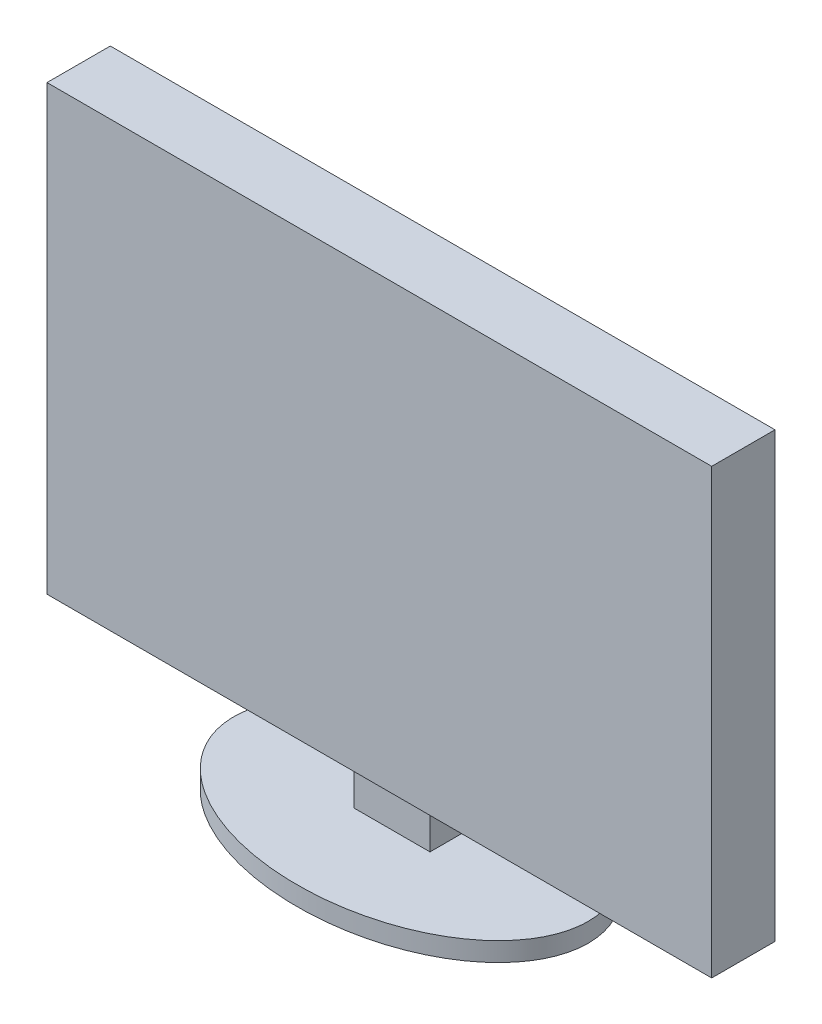
SolidWorks part; units mm, degrees
ref_plane "Front Plane" through (0, 0, 0) normal (0, 0, 1) x (1, 0, 0)
ref_plane "Top Plane" through (0, 0, 0) normal (0, 1, 0) x (1, 0, 0)
ref_plane "Right Plane" through (0, 0, 0) normal (1, 0, 0) x (0, 0, -1)
sketch "Sketch1" plane through (0, 0, 0) normal (0, 1, 0) x (1, 0, 0)
  ellipse E0 centre (0, 0) end of major axis (140, 0) minor radius 90
  dimension "D1" = 280
  dimension "D2" = 180
extrude "Boss-Extrude1" add sketch "Sketch1" along normal blind 15
sketch "Sketch2" plane through (0, 15, 0) normal (0, 1, 0) x (1, 0, 0)
  line L1 (-30, -15) -> (30, -15)
  line L2 (-30, -15) -> (-30, 15)
  line L3 (-30, 15) -> (30, 15)
  line L4 (30, -15) -> (30, 15)
  line L5 (-30, -15) -> (30, 15) construction
  line L6 (-30, 15) -> (30, -15) construction
  point P0 (0, 0)
  dimension "D1" = 60
  dimension "D2" = 30
extrude "Boss-Extrude2" add sketch "Sketch2" along normal blind 35
sketch "Sketch3" plane through (0, 50, 0) normal (0, 1, 0) x (1, 0, 0)
  line L1 (-262.5, -25) -> (262.5, -25)
  line L2 (-262.5, -25) -> (-262.5, 25)
  line L3 (-262.5, 25) -> (262.5, 25)
  line L4 (262.5, -25) -> (262.5, 25)
  line L5 (-262.5, -25) -> (262.5, 25) construction
  line L6 (-262.5, 25) -> (262.5, -25) construction
  point P0 (0, 0)
  dimension "D1" = 525
  dimension "D2" = 50
extrude "Boss-Extrude3" add sketch "Sketch3" along normal blind 350
